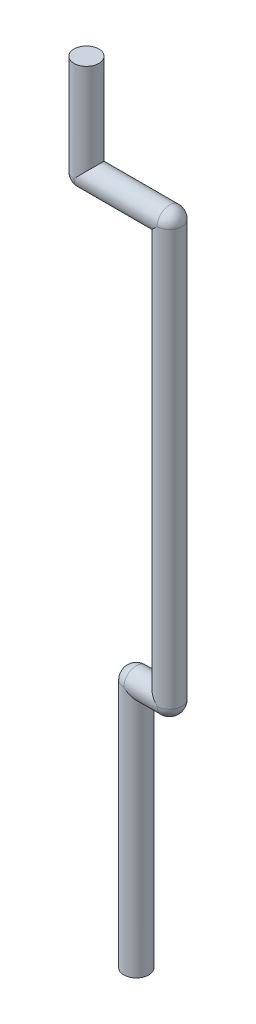
SolidWorks part; units mm, degrees
ref_plane "前视基准面" through (0, 0, 0) normal (0, 0, 1) x (1, 0, 0)
ref_plane "上视基准面" through (0, 0, 0) normal (0, 1, 0) x (1, 0, 0)
ref_plane "右视基准面" through (0, 0, 0) normal (1, 0, 0) x (0, 0, -1)
other "Configuration Table"
sketch "草图1" plane through (0, 0, 0) normal (0, 1, 0) x (1, 0, 0)
  circle A0 centre (0, 0) radius 0.75
  dimension "D1" = 1.5
extrude "凸台-拉伸1" add sketch "草图1" along normal blind 15
sketch "草图2" plane through (0, 0, 0) normal (0, 0, 1) x (1, 0, 0)
  line L2 (0.75, 15) -> (-0.75, 15) construction
  line L3 (0, 15.75) -> (0, 14.25)
  arc A1 (0, 14.25) -> (0, 15.75) centre (0, 15) ccw
revolve "旋转1" add sketch "草图2" angle 360 about L3
sketch "草图3" plane through (0, 0, 0) normal (1, 0, 0) x (0, 0, -1)
  line L0 (-0.75, 15) -> (0.75, 15) construction
  circle A0 centre (0, 15) radius 0.75
  dimension "D1" = 1.5
extrude "凸台-拉伸2" add sketch "草图3" along normal blind 2
sketch "草图4" plane through (2, 0, 0) normal (1, 0, 0) x (0, 0, -1)
  line L0 (0, 15.75) -> (0, 14.25)
  arc A0 (0, 14.25) -> (0, 15.75) centre (0, 15) ccw
  circle A1 centre (0, 15) radius 0.75 construction
  dimension "D1" = 0.75
revolve "旋转2" add sketch "草图4" angle 360 about L0
ref_plane "基准面1" through (0, 15, 0) normal (0, 1, 0) x (1, 0, 0)
sketch "草图5" plane through (0, 15, 0) normal (0, 1, 0) x (1, 0, 0)
  line L0 (2, 0.75) -> (2, -0.75) construction
  circle A0 centre (2, 0) radius 0.75
  dimension "D1" = 1.5
extrude "凸台-拉伸3" add sketch "草图5" along normal blind 25
sketch "草图6" plane through (0, 40, 0) normal (0, 1, 0) x (1, 0, 0)
  line L0 (2, 0.75) -> (2, -0.75)
  arc A0 (2, -0.75) -> (2, 0.75) centre (2, 0) ccw
revolve "旋转3" add sketch "草图6" angle 360 about L0
ref_plane "基准面3" through (2, 0, 0) normal (1, 0, 0) x (0, 0, -1)
sketch "草图7" plane through (2, 0, 0) normal (1, 0, 0) x (0, 0, -1)
  line L2 (-0.75, 40) -> (0.75, 40) construction
  line L3 (0, 40) -> (0, 15) construction
  line L4 (0.825, 15) -> (-0.825, 15) construction
  circle A1 centre (0, 40) radius 0.75
  dimension "D1" = 1.5
extrude "凸台-拉伸4" add sketch "草图7" against normal blind 5
sketch "草图8" plane through (-3, 0, 0) normal (-1, 0, 0) x (0, 0, 1)
  line L0 (-0.75, 40) -> (0.75, 40)
  arc A0 (0.75, 40) -> (-0.75, 40) centre (0, 40) ccw
  dimension "D1" = 0.75
revolve "旋转5" add sketch "草图8" angle 360 about L0
sketch "草图9" plane through (0, 15, 0) normal (0, 1, 0) x (1, 0, 0)
  line L0 (-3, 0.75) -> (-3, -0.75) construction
  circle A0 centre (-3, 0) radius 0.75
  dimension "D1" = 1.5
extrude "凸台-拉伸5" add sketch "草图9" along normal blind 6 from offset 25
